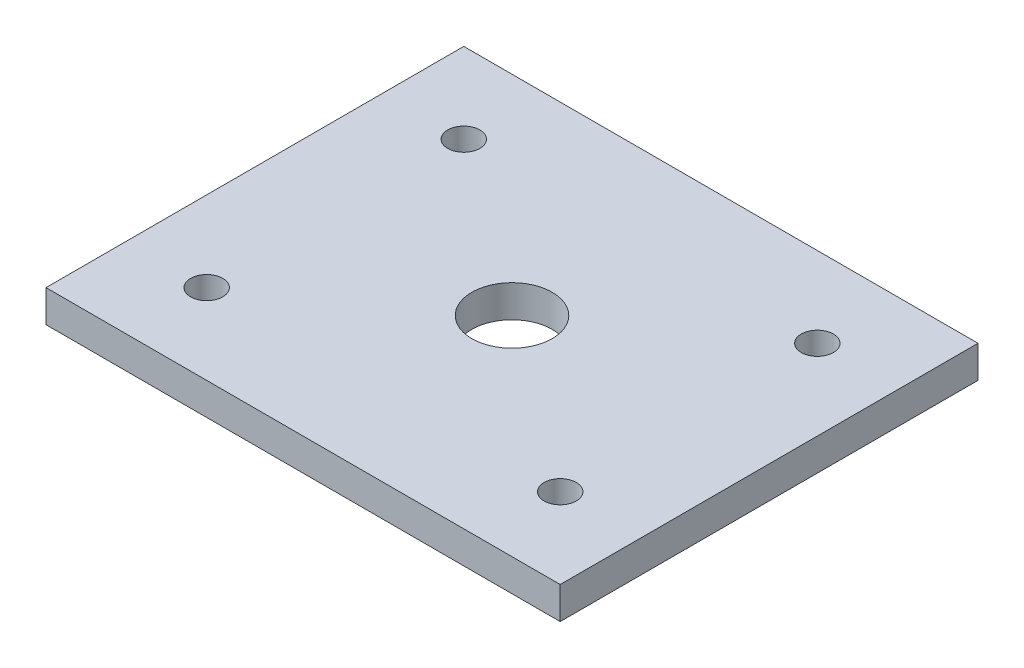
SolidWorks part; units mm, degrees
ref_plane "Front Plane" through (0, 0, 0) normal (0, 0, 1) x (1, 0, 0)
ref_plane "Top Plane" through (0, 0, 0) normal (0, 1, 0) x (1, 0, 0)
ref_plane "Right Plane" through (0, 0, 0) normal (1, 0, 0) x (0, 0, -1)
sketch "Sketch1" plane through (0, 0, 0) normal (0, 1, 0) x (1, 0, 0)
  line L1 (-32, -26) -> (32, -26)
  line L2 (-32, -26) -> (-32, 26)
  line L3 (-32, 26) -> (32, 26)
  line L4 (32, -26) -> (32, 26)
  circle A0 centre (0, 0) radius 5
  circle A1 centre (-22, -16) radius 2
  circle A2 centre (22, -16) radius 2
  circle A3 centre (-22, 16) radius 2
  circle A4 centre (22, 16) radius 2
extrude "Plate_Extrude" add sketch "Sketch1" along normal blind 4
equation "\"ValveDiameter\" = 50mm"
equation "\"MotorGearTeeth\" = 40"
equation "\"OutputGearTeeth\" = 80"
equation "\"GearModule\" = 1.5mm"
equation "\"PressureAngle\" = 20deg"
equation "\"GearCenterDistance\" = 90mm"
equation "\"GearWidth\" = 18mm"
equation "\"OutputShaftDiameter\" = 20mm"
equation "\"BearingOD\" = 47mm"
equation "\"BearingWidth\" = 14mm"
equation "\"PlateThickness\" = 6mm"
equation "\"ValveRotation\" = 90deg"
